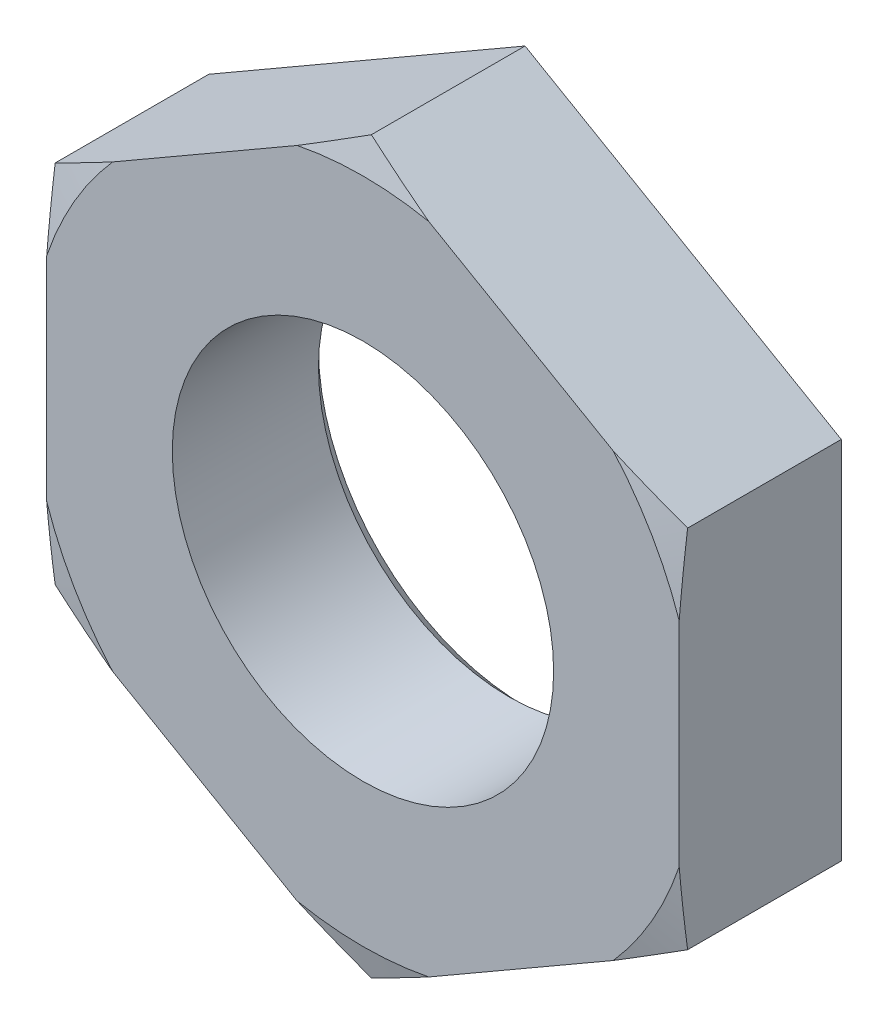
SolidWorks part; units mm, degrees
ref_plane "基准面1" through (0, 0, 0) normal (0, 0, 1) x (1, 0, 0)
ref_plane "基准面2" through (0, 0, 0) normal (0, 1, 0) x (1, 0, 0)
ref_plane "基准面3" through (0, 0, 0) normal (1, 0, 0) x (0, 0, -1)
sketch "尺寸草图" plane through (0, 0, 0) normal (0, 0, 1) x (1, 0, 0)
  line L0 (0, 0) -> (9.2444, 0)
  point P3 (4, 0)
  point P4 (1.7, 0)
  point P5 (7, 0)
  point P6 (5.1072, 0)
  point P7 (4.0801, 0)
  point P8 (7.66, 0)
  dimension "D" = 4
  dimension "e" = 7.66
  dimension "m" = 1.7
  dimension "s" = 7
sketch "草图1" plane through (0, 0, 0) normal (0, 0, 1) x (1, 0, 0)
  line L0 (0, 20.0172) -> (0, -14.298) construction
  line L1 (-13.2257, 0) -> (13.2257, 0) construction
  line L3 (0, 3.83) -> (-3.3169, 1.915)
  line L4 (-3.3169, 1.915) -> (-3.3169, -1.915)
  line L5 (-3.3169, -1.915) -> (0, -3.83)
  line L6 (0, -3.83) -> (3.3169, -1.915)
  line L7 (3.3169, -1.915) -> (3.3169, 1.915)
  line L8 (3.3169, 1.915) -> (0, 3.83)
  circle A0 centre (0, 0) radius 3.3169 construction
  circle A1 centre (0, 0) radius 2
  dimension "D" = 4
  dimension "e" = 7.66
extrude "基体-拉伸" add sketch "草图1" along normal blind 1.7
cosmetic thread "装饰螺纹线1"
chamfer "倒角1" distance 0.1667 angle 45 1 edges at (2, 0, 0)
sketch "草图2" plane through (0, 0, 1.7) normal (0, 0, 1) x (1, 0, 0)
  circle A0 centre (0, 0) radius 3.5
  dimension "s" = 7
extrude "切除-拉伸1" cut sketch "草图2" against normal through all draft 75 flip side to cut
equation "\"D@草图1\" = \"D@尺寸草图\""
equation "\"m@基体-拉伸\" = \"m@尺寸草图\""
equation "\"e@草图1\" = \"e@尺寸草图\""
equation "\"s@草图2\" = \"s@尺寸草图\""
equation "\"D1@倒角1\" = \"D@草图1\"/24"
equation "\"D2@装饰螺纹线1\" = \"D@草图1\"-\"D@草图1\"/24"
